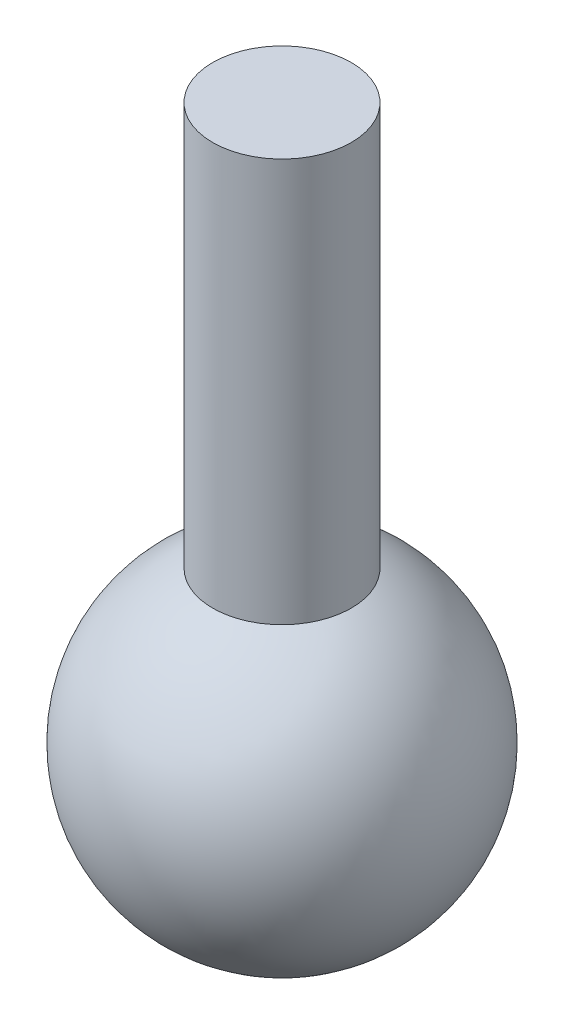
SolidWorks part; units mm, degrees
ref_plane "Front Plane" through (0, 0, 0) normal (0, 0, 1) x (1, 0, 0)
ref_plane "Top Plane" through (0, 0, 0) normal (0, 1, 0) x (1, 0, 0)
ref_plane "Right Plane" through (0, 0, 0) normal (1, 0, 0) x (0, 0, -1)
sketch "Sketch1" plane through (0, 0, 0) normal (1, 0, 0) x (0, 0, -1)
  line L0 (0, 6) -> (0, -6)
  arc A0 (0, -6) -> (0, 6) centre (0, 0) ccw
revolve "Revolve1" add sketch "Sketch1" angle 360 about L0
sketch "Sketch2" plane through (0, 0, 0) normal (0, 1, 0) x (1, 0, 0)
  circle A0 centre (0, 0) radius 2.5
extrude "Boss-Extrude1" add sketch "Sketch2" along normal blind 20
